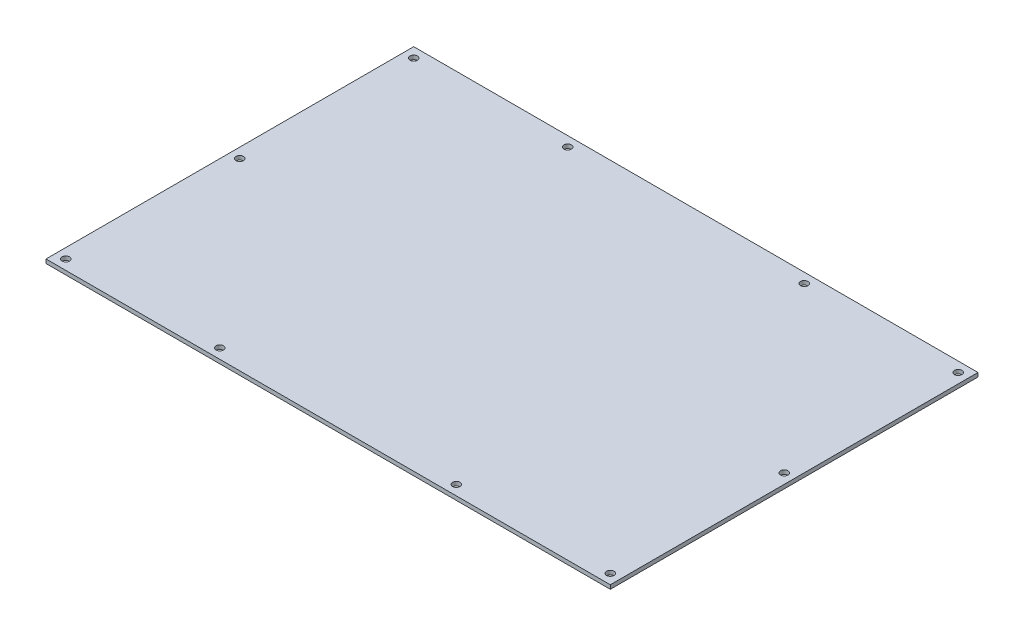
SolidWorks part; units mm, degrees
ref_plane "Front Plane" through (0, 0, 0) normal (0, 0, 1) x (1, 0, 0)
ref_plane "Top Plane" through (0, 0, 0) normal (0, 1, 0) x (1, 0, 0)
ref_plane "Right Plane" through (0, 0, 0) normal (1, 0, 0) x (0, 0, -1)
sketch "Sketch1" plane through (0, 0, 0) normal (0, 1, 0) x (1, 0, 0)
  line L13 (0, 0) -> (0, 148.48)
  line L14 (227.86, 148.48) -> (0, 148.48)
  line L16 (227.86, 0) -> (0, 0)
  line L17 (223.86, 144.48) -> (223.86, 148.48) construction
  line L18 (223.86, 144.48) -> (227.86, 144.48) construction
  line L19 (223.86, 144.48) -> (161.68, 144.48) construction
  line L20 (161.68, 144.48) -> (66.18, 144.48) construction
  line L21 (227.86, 148.48) -> (227.86, 0)
  line L22 (66.18, 144.48) -> (4, 144.48) construction
  line L23 (4, 144.48) -> (4, 4) construction
  line L24 (4, 4) -> (223.86, 4) construction
  line L25 (223.86, 4) -> (223.86, 144.48) construction
  line L26 (161.68, 144.48) -> (161.68, 4) construction
  line L27 (66.18, 4) -> (66.18, 144.48) construction
  circle A2 centre (223.86, 74.24) radius 1.5
  circle A3 centre (4, 74.24) radius 1.5
  circle A4 centre (66.18, 4) radius 1.5
  circle A5 centre (161.68, 4) radius 1.5
  circle A6 centre (161.68, 144.48) radius 1.5
  circle A7 centre (66.18, 144.48) radius 1.5
  circle A8 centre (223.86, 4) radius 1.5
  circle A9 centre (4, 4) radius 1.5
  circle A10 centre (4, 144.48) radius 1.5
  circle A11 centre (223.86, 144.48) radius 1.5
  dimension "D10" = 3
  dimension "D19" = 3
  dimension "D11" = 62.18
  dimension "D12" = 95.5
  dimension "D13" = 62.18
  dimension "D14" = 140.48
  dimension "D15" = 148.48
  dimension "D16" = 227.86
  dimension "D17" = 4
  dimension "D18" = 4
extrude "Boss-Extrude2" add sketch "Sketch1" along normal blind 1.6
